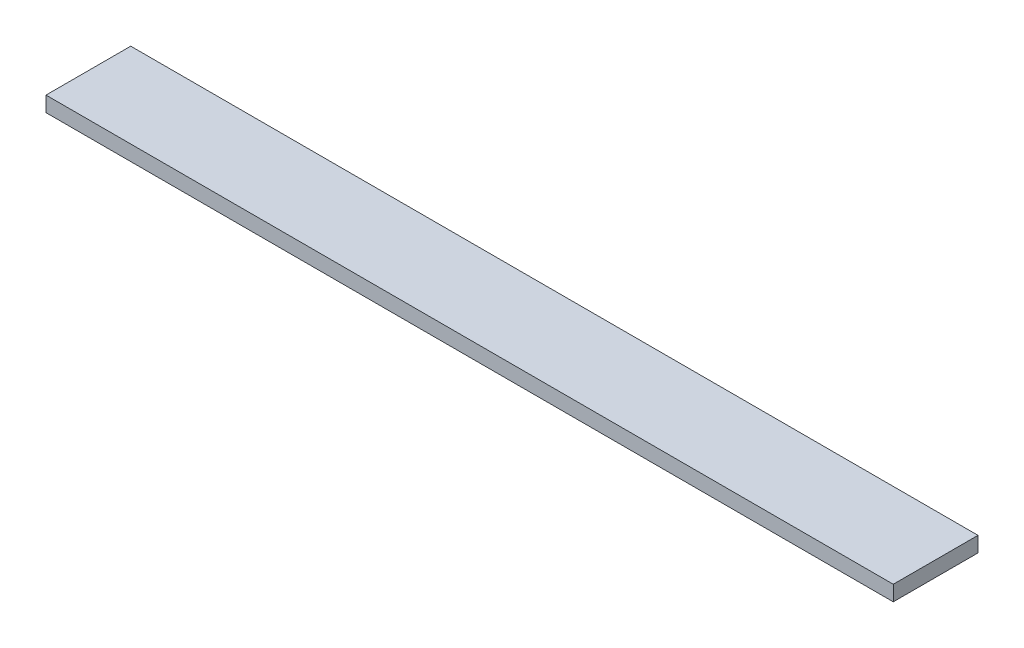
SolidWorks part; units mm, degrees
ref_plane "Front Plane" through (0, 0, 0) normal (0, 0, 1) x (1, 0, 0)
ref_plane "Top Plane" through (0, 0, 0) normal (0, 1, 0) x (1, 0, 0)
ref_plane "Right Plane" through (0, 0, 0) normal (1, 0, 0) x (0, 0, -1)
sketch "Esquisse1" plane through (0, 0, 0) normal (0, 1, 0) x (1, 0, 0)
  line L1 (-500, 50) -> (500, 50)
  line L2 (-500, 50) -> (-500, -50)
  line L3 (-500, -50) -> (500, -50)
  line L4 (500, 50) -> (500, -50)
  line L5 (-500, 50) -> (500, -50) construction
  line L6 (-500, -50) -> (500, 50) construction
  point P0 (0, 0)
extrude "Boss.-Extru.1" add sketch "Esquisse1" along normal blind 18
